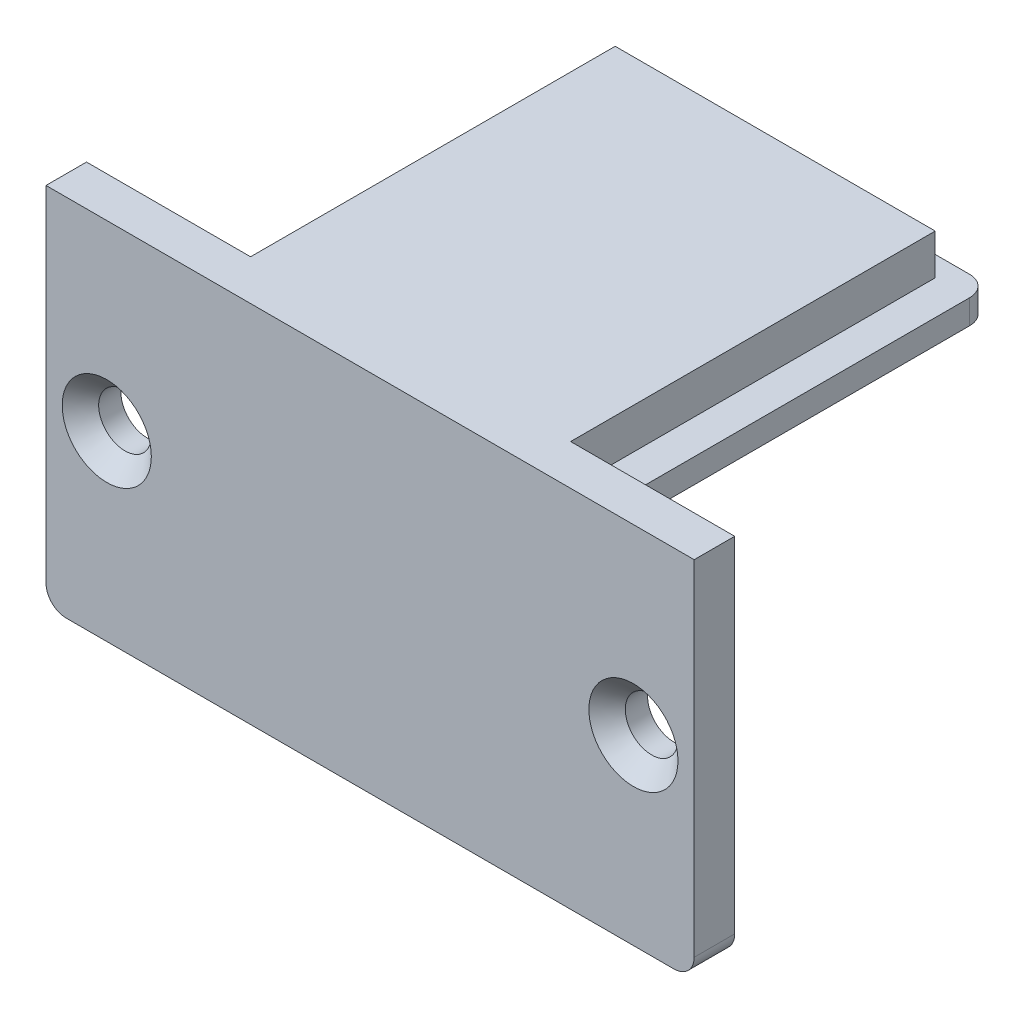
SolidWorks part; units mm, degrees
ref_plane "Plan de face" through (0, 0, 0) normal (0, 0, 1) x (1, 0, 0)
ref_plane "Plan de dessus" through (0, 0, 0) normal (0, 1, 0) x (1, 0, 0)
ref_plane "Plan de droite" through (0, 0, 0) normal (1, 0, 0) x (0, 0, -1)
sketch "Esquisse1" plane through (0, 0, 0) normal (0, 0, 1) x (1, 0, 0)
  line L1 (-16, -9) -> (16, -9)
  line L2 (-16, -9) -> (-16, 9)
  line L3 (-16, 9) -> (16, 9)
  line L4 (16, -9) -> (16, 9)
  line L5 (-16, -9) -> (16, 9) construction
  line L6 (-16, 9) -> (16, -9) construction
  point P0 (0, 0)
  dimension "D1" = 32
  dimension "D2" = 18
extrude "Boss.-Extru.1" add sketch "Esquisse1" along normal blind 2
sketch "Esquisse2" plane through (0, 0, 0) normal (0, 0, -1) x (-1, 0, 0)
  line L0 (-16, 9) -> (16, 9) construction
  line L1 (-9.5, -7) -> (9.5, -7)
  line L2 (-9.5, -7) -> (-9.5, 7)
  line L3 (-9.5, 7) -> (9.5, 7)
  line L4 (9.5, -7) -> (9.5, 7)
  line L5 (-9.5, -7) -> (9.5, 7) construction
  line L6 (-9.5, 7) -> (9.5, -7) construction
  point P0 (0, 0)
  dimension "D1" = 2
  dimension "D2" = 19
extrude "Boss.-Extru.2" add sketch "Esquisse2" along normal blind 1.4
fillet "Congé1" [suppressed] radius 1
fillet "Congé2" [suppressed] radius 0.6
fillet "Congé3" [suppressed] radius 1
hole_wizard "Fraisage pour vis à tête fraisée M21" positions "Esquisse4" profile "Esquisse5" countersink size "M2" standard "ISO" end condition through all
sketch "Esquisse4" plane through (0, 0, 2) normal (0, 0, 1) x (1, 0, 0)
  line L0 (-16, 0) -> (16, 0) construction
  point P0 (-13, 0)
  dimension "D1" = 13
sketch "Esquisse5" plane through (-13, 0, 2) normal (1, 0, 0) x (0, -1, 0)
  line L0 (0, 0) -> (0, 3.4)
  line L1 (0, 3.4) -> (1.3, 3.4)
  line L2 (1.3, 3.4) -> (1.3, 0.9)
  line L3 (1.3, 0.9) -> (2.2, 0)
  line L5 (2.2, 0) -> (0, 0)
  line L6 (-1.3, 0.9) -> (-2.2, 0) construction
  line L11 (0, -6.35) -> (0, 107.95) construction
  dimension "Diamètre du perçage jusqu'au prochain" = 2.6
  dimension "Profondeur du perçage jusqu'au prochain" = 3.4
  dimension "Diamètre du fraisage entrant" = 4.4
  dimension "Angle du fraisage entrant" = 90
mirror "Symétrie1" about plane through (0, 0, 0) normal (1, 0, 0) of "Fraisage pour vis à tête fraisée M21"
sketch "Esquisse6" plane through (0, 0, 0) normal (0, 0, -1) x (-1, 0, 0)
  line L0 (0, 0) -> (0, 12.4758) construction
  line L1 (9.5, 7) -> (-9.5, 7) construction
  line L2 (-7.9, 9) -> (7.9, 9)
  line L3 (-7.9, 9) -> (-7.9, 7)
  line L4 (-7.9, 7) -> (7.9, 7)
  line L5 (7.9, 9) -> (7.9, 7)
  line L6 (-7.9, 9) -> (7.9, 7) construction
  line L7 (-7.9, 7) -> (7.9, 9) construction
  line L8 (-16, 9) -> (16, 9) construction
  point P3 (0, 8)
  dimension "D1" = 15.8
extrude "Boss.-Extru.3" add sketch "Esquisse6" along normal blind 18
sketch "Esquisse7" plane through (0, 0, 2) normal (0, 0, 1) x (1, 0, 0)
  line L5 (0, 9) -> (0, 3.4178) construction
  line L6 (9.6, 7) -> (-9.6, 7)
  line L7 (9.6, 7) -> (9.6, 5.8)
  line L8 (9.6, 5.8) -> (-9.6, 5.8)
  line L9 (-9.6, 7) -> (-9.6, 5.8)
  line L10 (-7.9, 9) -> (7.9, 9) construction
  line L11 (-7.9, 7) -> (7.9, 7) construction
  dimension "D1" = 19.2
  dimension "D2" = 1.2
extrude "Boss.-Extru.4" add sketch "Esquisse7" against normal blind 21
fillet "Congé5" radius 1 4 edges at (16, -9, 1) (-16, -9, 1) (9.6, 6.4, -19) (-9.6, 6.4, -19)
